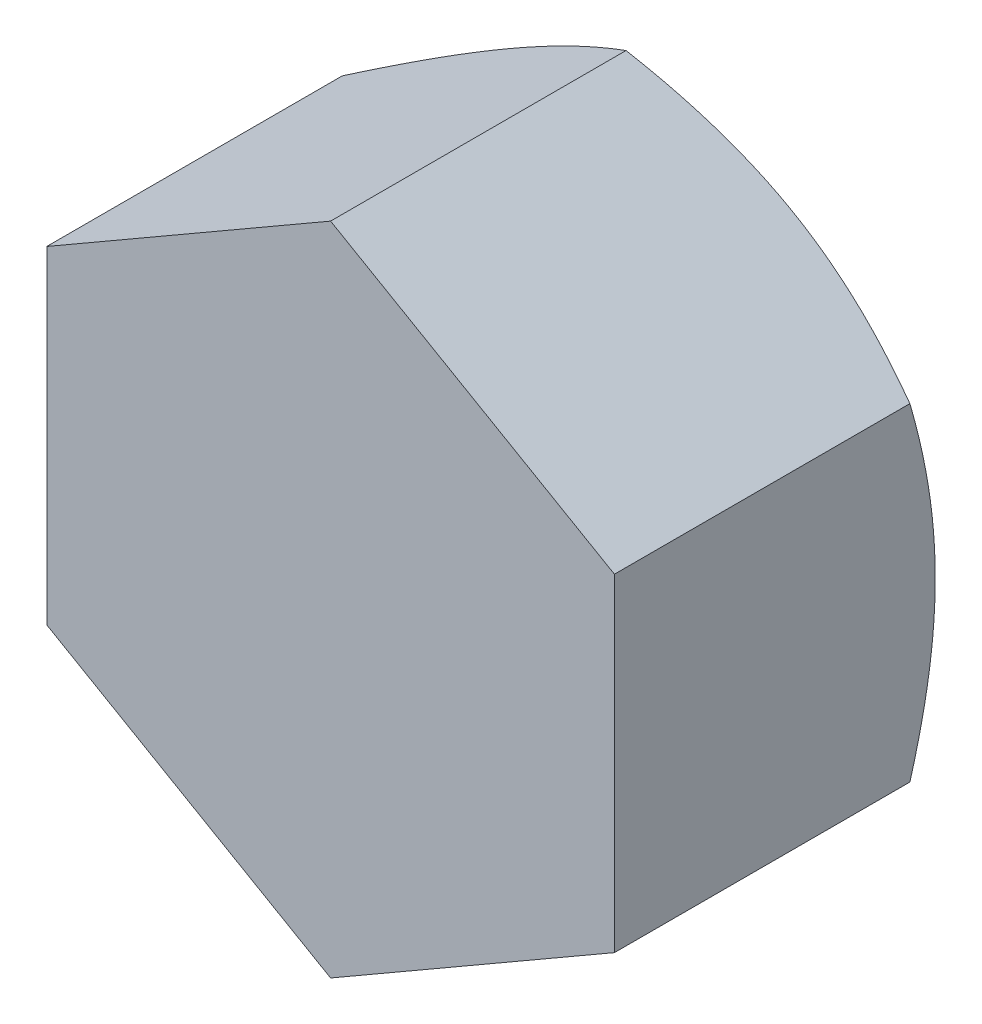
SolidWorks part; units mm, degrees
ref_plane "前视基准面" through (0, 0, 0) normal (0, 0, 1) x (1, 0, 0)
ref_plane "上视基准面" through (0, 0, 0) normal (0, 1, 0) x (1, 0, 0)
ref_plane "右视基准面" through (0, 0, 0) normal (1, 0, 0) x (0, 0, -1)
other "Configuration Table"
sketch "草图1" plane through (0, 0, 0) normal (0, 0, 1) x (1, 0, 0)
  line L1 (25, -14.4338) -> (25, 14.4338)
  line L2 (25, 14.4338) -> (0, 28.8675)
  line L3 (0, 28.8675) -> (-25, 14.4338)
  line L4 (-25, 14.4338) -> (-25, -14.4338)
  line L5 (-25, -14.4338) -> (0, -28.8675)
  line L6 (0, -28.8675) -> (25, -14.4338)
  circle A0 centre (0, 0) radius 25 construction
  point P1 (0, 0)
  dimension "D1" = 50
extrude "凸台-拉伸1" add sketch "草图1" along normal blind 30
sketch "草图2" plane through (0, 0, 0) normal (1, 0, 0) x (0, 0, -1)
  line L0 (10.7041, 0) -> (-50.5719, 0) construction
  line L1 (-4, 37.5859) -> (-4, -33.653) construction
  line L2 (0, 14.4338) -> (0, 28.8675) construction
  line L3 (-4, 28.9085) -> (0.6138, 20.9171)
  line L4 (0.6138, 20.9171) -> (0.6138, 32.8344)
  line L5 (0.6138, 32.8344) -> (-4, 28.9085)
  dimension "D1" = 4
  dimension "D2" = 30
revolve "切除-旋转1" cut sketch "草图2" angle 360 about L0
